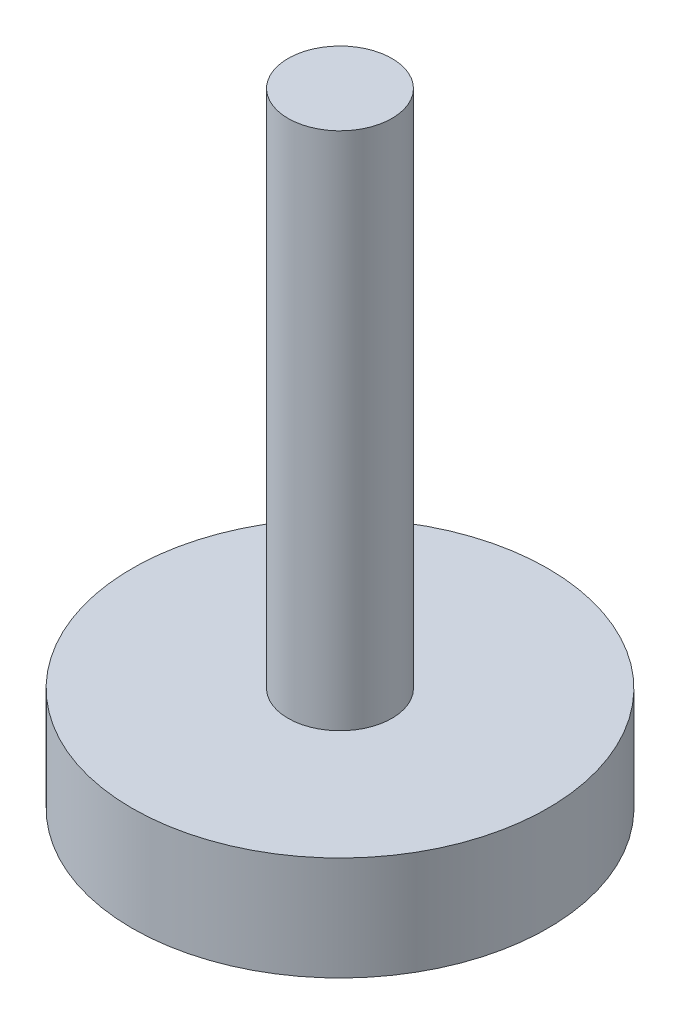
SolidWorks part; units mm, degrees
ref_plane "前视基准面" through (0, 0, 0) normal (0, 0, 1) x (1, 0, 0)
ref_plane "上视基准面" through (0, 0, 0) normal (0, 1, 0) x (1, 0, 0)
ref_plane "右视基准面" through (0, 0, 0) normal (1, 0, 0) x (0, 0, -1)
other "Configuration Table"
sketch "草图1" plane through (0, 0, 0) normal (0, 1, 0) x (1, 0, 0)
  circle A0 centre (0, 0) radius 4
extrude "凸台-拉伸1" add sketch "草图1" along normal blind 2
sketch "草图2" plane through (0, 2, 0) normal (0, 1, 0) x (1, 0, 0)
  circle A0 centre (0, 0) radius 1
extrude "凸台-拉伸2" add sketch "草图2" along normal blind 10
